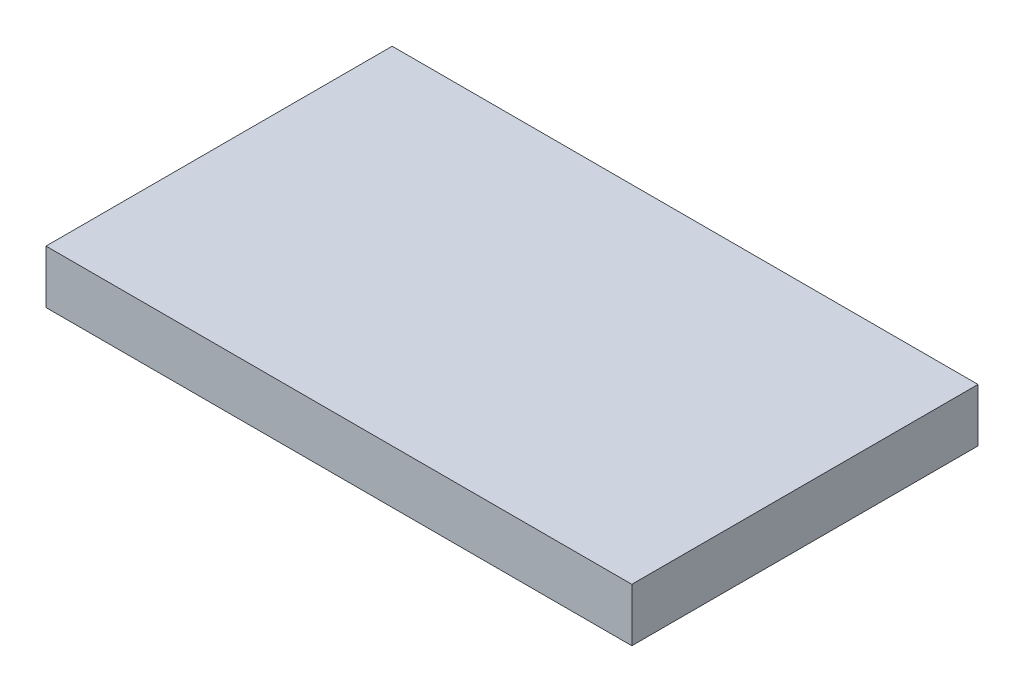
SolidWorks part; units mm, degrees
ref_plane "Front Plane" through (0, 0, 0) normal (0, 0, 1) x (1, 0, 0)
ref_plane "Top Plane" through (0, 0, 0) normal (0, 1, 0) x (1, 0, 0)
ref_plane "Right Plane" through (0, 0, 0) normal (1, 0, 0) x (0, 0, -1)
sketch "Sketch1" plane through (0, 0, 0) normal (0, 1, 0) x (1, 0, 0)
  line L1 (-11, 6.5) -> (11, 6.5)
  line L2 (-11, 6.5) -> (-11, -6.5)
  line L3 (-11, -6.5) -> (11, -6.5)
  line L4 (11, 6.5) -> (11, -6.5)
  line L5 (-11, 6.5) -> (11, -6.5) construction
  line L6 (-11, -6.5) -> (11, 6.5) construction
  point P0 (0, 0)
  dimension "D1" = 22
  dimension "D2" = 13
extrude "Boss-Extrude1" add sketch "Sketch1" along normal mid plane 2
